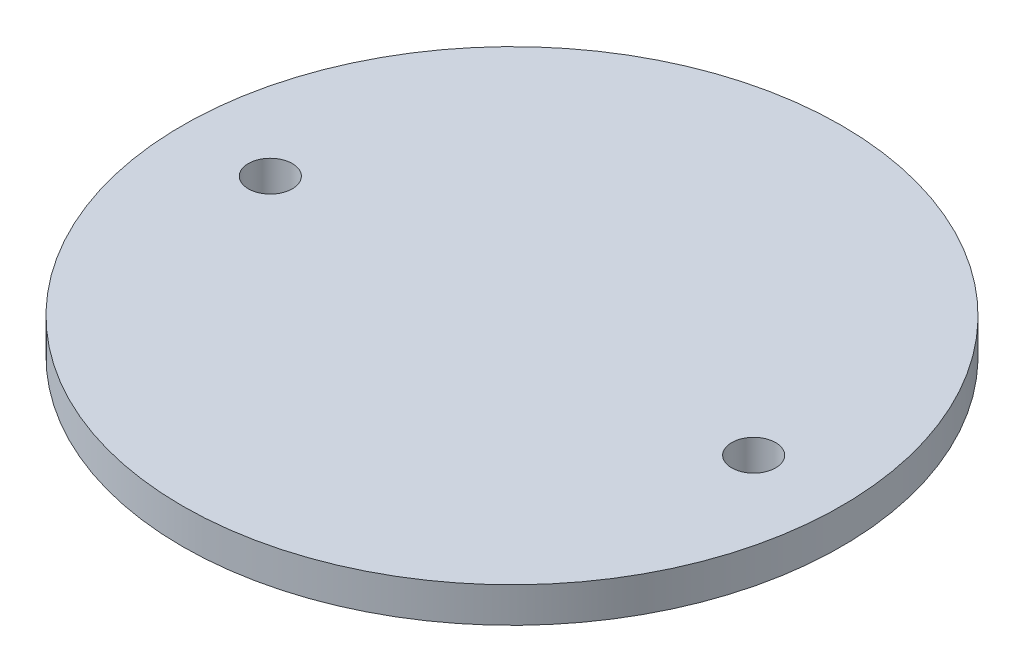
SolidWorks part; units mm, degrees
ref_plane "Front Plane" through (0, 0, 0) normal (0, 0, 1) x (1, 0, 0)
ref_plane "Top Plane" through (0, 0, 0) normal (0, 1, 0) x (1, 0, 0)
ref_plane "Right Plane" through (0, 0, 0) normal (1, 0, 0) x (0, 0, -1)
sketch "Sketch1" plane through (0, 0, 0) normal (0, 1, 0) x (1, 0, 0)
  circle A0 centre (0, 0) radius 37.5
  dimension "D1" = 75
extrude "Boss-Extrude1" add sketch "Sketch1" along normal blind 4
sketch "Sketch2" plane through (0, 4, 0) normal (0, 1, 0) x (1, 0, 0)
  line L0 (-37.5, 0) -> (37.5, 0) construction
  line L1 (0, 37.5) -> (0, -37.5) construction
  circle A0 centre (0, 0) radius 37.5 construction
  circle A1 centre (-27.5, 0) radius 2.5
  circle A2 centre (27.5, 0) radius 2.5
  dimension "D1" = 5
  dimension "D2" = 55
extrude "Cut-Extrude1" cut sketch "Sketch2" against normal through all
